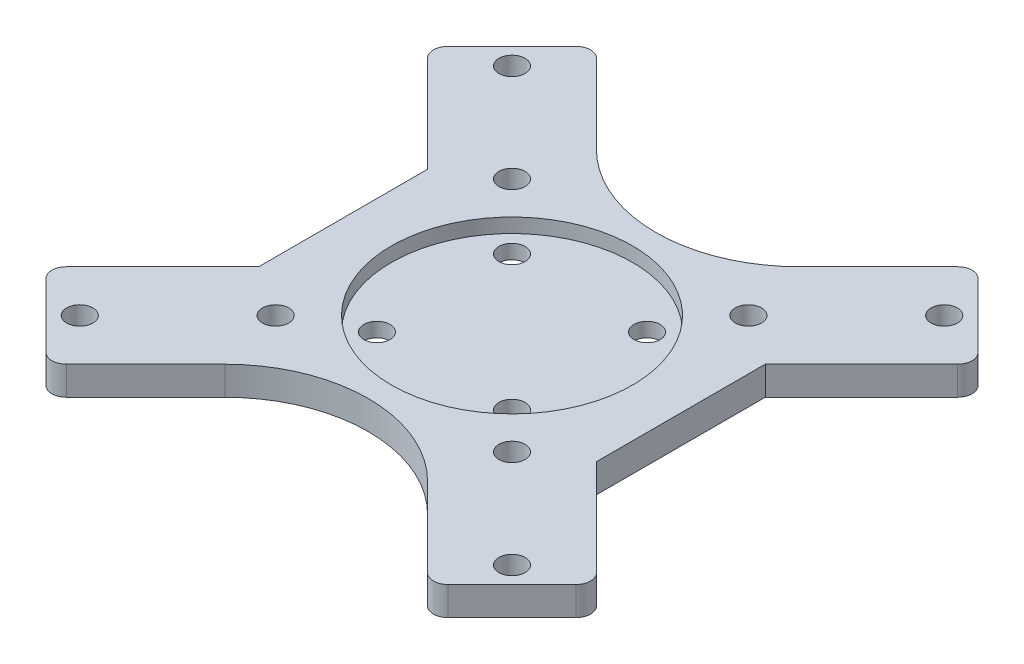
SolidWorks part; units mm, degrees
ref_plane "Front Plane" through (0, 0, 0) normal (0, 0, 1) x (1, 0, 0)
ref_plane "Top Plane" through (0, 0, 0) normal (0, 1, 0) x (1, 0, 0)
ref_plane "Right Plane" through (0, 0, 0) normal (1, 0, 0) x (0, 0, -1)
sketch "Sketch1" plane through (0, 0, 0) normal (0, 1, 0) x (1, 0, 0)
  line L26 (-57.6292, 39.9515) -> (-39.9515, 57.6292)
  line L27 (-39.9515, 57.6292) -> (-21.2132, 38.8909)
  line L28 (21.2132, 38.8909) -> (39.9515, 57.6292)
  line L29 (39.9515, 57.6292) -> (57.6292, 39.9515)
  line L30 (57.6292, 39.9515) -> (35.3553, 17.6777)
  line L31 (35.3553, -17.6777) -> (57.6292, -39.9515)
  line L32 (57.6292, -39.9515) -> (39.9515, -57.6292)
  line L33 (39.9515, -57.6292) -> (21.2132, -38.8909)
  line L34 (-21.2132, -38.8909) -> (-39.9515, -57.6292)
  line L35 (-39.9515, -57.6292) -> (-57.6292, -39.9515)
  line L36 (-57.6292, -39.9515) -> (-35.3553, -17.6777)
  line L37 (-35.3553, 17.6777) -> (-57.6292, 39.9515)
  line L38 (0, 0) -> (0, 76.4028) construction
  line L39 (-48.7904, 48.7904) -> (48.7904, -48.7904) construction
  line L40 (48.7904, 48.7904) -> (-48.7904, -48.7904) construction
  line L41 (-35.3553, -17.6777) -> (-35.3553, 17.6777)
  line L42 (35.3553, 17.6777) -> (35.3553, -17.6777)
  line L43 (-35.3553, 0) -> (35.3553, 0) construction
  line L44 (-24.75, 24.75) -> (0, 0) construction
  circle A11 centre (0, 0) radius 64 construction
  circle A12 centre (-45.2548, 45.2548) radius 2.75
  circle A13 centre (45.2548, 45.2548) radius 2.75
  circle A14 centre (45.2548, -45.2548) radius 2.75
  circle A15 centre (-45.2548, -45.2548) radius 2.75
  arc A16 (21.2132, -38.8909) -> (-21.2132, -38.8909) centre (0, -60.1041) ccw
  arc A17 (-21.2132, 38.8909) -> (21.2132, 38.8909) centre (0, 60.1041) ccw
  circle A18 centre (-24.75, 24.75) radius 2.75
  circle A19 centre (-24.75, -24.75) radius 2.75
  circle A20 centre (24.75, -24.75) radius 2.75
  circle A21 centre (24.75, 24.75) radius 2.75
  circle A22 centre (0, 0) radius 20 construction
  circle A24 centre (-14.1421, 14.1421) radius 2.75
  circle A25 centre (14.1421, 14.1421) radius 2.75
  circle A26 centre (14.1421, -14.1421) radius 2.75
  circle A27 centre (-14.1421, -14.1421) radius 2.75
  point P6 (17.6777, 0)
  point P12 (-17.6777, 0)
  point P19 (0, 0)
  point P53 (35.3553, 0)
  dimension "D1" = 45
  dimension "D3" = 138
  dimension "D4" = 138
  dimension "D6" = 5.5
  dimension "D5" = 128
  dimension "D7" = 30
  dimension "D9" = 49.5
  dimension "D14" = 5.5
  dimension "D15" = 40
  dimension "D16" = 5.5
  dimension "D2" = 25
  dimension "D8" = 35.3553
  dimension "D12" = 49.5
  dimension "D13" = 45
  dimension "D17" = 4
extrude "Boss-Extrude1" add sketch "Sketch1" along normal blind 6
fillet "Fillet1" radius 3 8 edges at (-57.6292, 3, 39.9515) (-39.9515, 3, 57.6292) (39.9515, 3, 57.6292) (57.6292, 3, 39.9515) (57.6292, 3, -39.9515) (39.9515, 3, -57.6292) (-39.9515, 3, -57.6292) (-57.6292, 3, -39.9515)
sketch "Sketch2" plane through (0, 6, 0) normal (0, 1, 0) x (1, 0, 0)
  circle A0 centre (0, 0) radius 25.25
  dimension "D1" = 50.5
extrude "Cut-Extrude1" cut sketch "Sketch2" against normal blind 3
